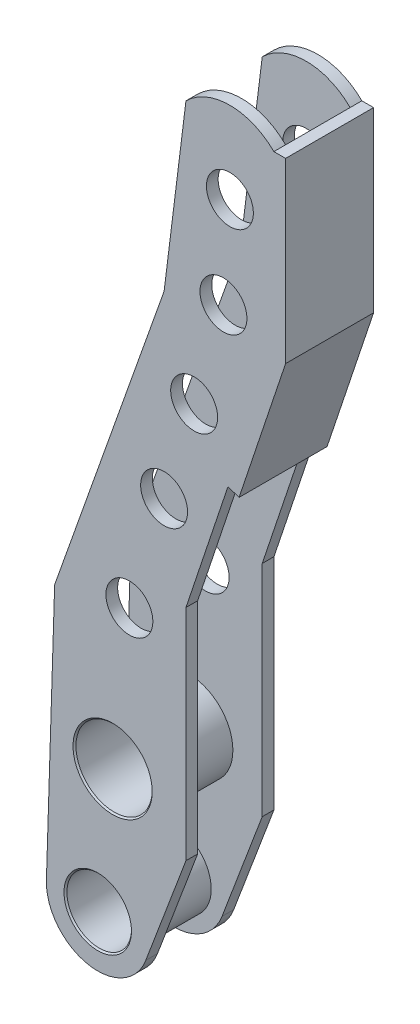
SolidWorks part; units mm, degrees
material "AISI 1020 Steel, Cold Rolled"
ref_plane "Front Plane" through (0, 0, 0) normal (0, 0, 1) x (1, 0, 0)
ref_plane "Top Plane" through (0, 0, 0) normal (0, 1, 0) x (1, 0, 0)
ref_plane "Right Plane" through (0, 0, 0) normal (1, 0, 0) x (0, 0, -1)
sketch "Sketch1" plane through (0, 0, 0) normal (0, 0, 1) x (1, 0, 0)
  line B0 (43.6562, 145.4782) -> (60.0385, 194.4865)
  line B1 (60.0385, 194.4865) -> (60.0385, 254.4271)
  line B2 (30.0781, 254.4271) -> (22.6293, 194.4865)
  line B3 (22.6293, 194.4865) -> (-14.6833, 89.2308)
  line B4 (-14.6833, 89.2308) -> (-14.6833, -0.057)
  line B5 (14.7807, -0.057) -> (30.0781, 30.1029)
  line B6 (30.0781, 30.1029) -> (30.0781, 104.8586)
  line B7 (30.0781, 104.8586) -> (43.6562, 145.4782)
  arc B8 (60.0385, 254.4271) -> (30.0781, 254.4271) centre (45.0583, 239.4469) ccw
  arc B9 (-14.6833, -0.057) -> (14.7807, -0.057) centre (0.0487, -0.057) ccw
  circle B10 centre (-5.2372, 41.2368) radius 3
  circle B11 centre (1.7318, 52.1805) radius 3
  circle B12 centre (21.4304, 50.1742) radius 3
  circle B13 centre (9.5747, 59.1115) radius 3
  circle B14 centre (1.7318, 67.8664) radius 3
  circle B15 centre (-5.2372, 59.1115) radius 3
  circle B16 centre (-4.9682, 76.648) radius 3
  circle B17 centre (10.1372, 104.8586) radius 3.7338
  circle B18 centre (1.7318, 107.7204) radius 4
  circle B19 centre (-4.5729, 25.5702) radius 4
  circle B20 centre (5.6027, 24.4116) radius 4
  circle B21 centre (19.4271, 25.5702) radius 4
  circle B22 centre (0.0487, -0.057) radius 5
  circle B23 centre (10.1372, 81.8976) radius 7.366
  circle B24 centre (22.6293, 133.2845) radius 7.366
  circle B25 centre (32.8774, 166.3648) radius 7.366
  circle B26 centre (42.8552, 200.5742) radius 7.366
  circle B27 centre (45.0583, 232.7881) radius 7.366
sketch_block_instance "break pedal-1"
sketch_block "break pedal"
sketch "Sketch2" plane through (0, 0, 0) normal (0, 0, 1) x (1, 0, 0)
  line L0 (30.0781, 30.1029) -> (30.0781, 104.8586) construction
  line L1 (30.0781, 104.8586) -> (43.6562, 145.4782) construction
  line L2 (43.6562, 145.4782) -> (60.0385, 194.4865) construction
  line L3 (60.0385, 194.4865) -> (60.0385, 254.4271) construction
  line L4 (30.0781, 254.4271) -> (22.6293, 194.4865) construction
  line L5 (22.6293, 194.4865) -> (-14.6833, 89.2308) construction
  line L6 (30.0781, 30.1029) -> (30.0781, 104.8586)
  line L7 (30.0781, 104.8586) -> (43.6562, 145.4782)
  line L8 (43.6562, 145.4782) -> (60.0385, 194.4865)
  line L9 (60.0385, 194.4865) -> (60.0385, 254.4271)
  line L10 (30.0781, 254.4271) -> (22.6293, 194.4865)
  line L11 (22.6293, 194.4865) -> (-14.6833, 89.2308)
  line L12 (30.0781, 30.1029) -> (16.3709, -6.184)
  line L13 (-14.6833, 89.2308) -> (-17.4912, 0.5538)
  line L14 (22.6293, 133.2845) -> (32.8774, 166.3648) construction
  line L15 (32.8774, 166.3648) -> (42.8552, 200.5742) construction
  line L16 (42.8552, 200.5742) -> (45.0583, 232.7881) construction
  line L17 (22.6293, 133.2845) -> (10.7925, 95.0759) construction
  line L18 (0, 0) -> (10.7925, 95.0759) construction
  circle A0 centre (0, 0) radius 12.7
  arc A1 (-17.4912, 0.5538) -> (16.3709, -6.184) centre (0, 0) ccw
  arc A2 (60.0385, 254.4271) -> (30.0781, 254.4271) centre (45.0583, 239.4469) ccw construction
  arc A3 (60.0385, 254.4271) -> (30.0781, 254.4271) centre (45.0583, 239.4469) ccw
  circle A4 centre (45.0583, 232.7881) radius 8
  circle A5 centre (42.8552, 200.5742) radius 8
  circle A6 centre (32.8774, 166.3648) radius 8
  circle A7 centre (22.6293, 133.2845) radius 8
  circle A9 centre (10.7925, 95.0759) radius 8
  circle A10 centre (5.0755, 44.7128) radius 15
  dimension "D1" = 35
  dimension "D2" = 25.4
  dimension "D3" = 16
  dimension "D4" = 40
  dimension "D5" = 45
  dimension "D6" = 30
extrude "Boss-Extrude1" add sketch "Sketch2" along normal blind 4 from offset 11
pattern_linear "LPattern1" count 2 spacing 26 along (0, 0, -1) of "Boss-Extrude1"
sketch "Sketch3" plane through (0, 0, 0) normal (0, 0, 1) x (1, 0, 0)
  line L0 (60.0385, 194.4865) -> (60.0385, 254.4271) construction
  line L1 (30.0781, 104.8586) -> (60.0385, 194.4865) construction
  line L2 (60.0385, 194.4865) -> (60.0385, 254.4271)
  line L3 (44.3933, 147.683) -> (60.0385, 194.4865)
  line L4 (48.1869, 146.4149) -> (64.0385, 193.8356)
  line L5 (64.0385, 193.8356) -> (64.0385, 254.4271)
  line L6 (60.0385, 254.4271) -> (64.0385, 254.4271)
  line L7 (44.3933, 147.683) -> (48.1869, 146.4149)
  line L8 (33.8718, 103.5905) -> (64.0385, 193.8356) construction
  line L9 (30.0781, 104.8586) -> (60.0385, 194.4865) construction
  dimension "D2" = 50
  dimension "D1" = 4
extrude "Boss-Extrude2" add sketch "Sketch3" along normal mid plane 30
chamfer "Chamfer1" [suppressed] distance 4 angle 45
sketch "Sketch4" plane through (0, 0, 0) normal (0, 0, 1) x (1, 0, 0)
  circle A0 centre (0, 0) radius 12.7
  circle A1 centre (5.0755, 44.7128) radius 15
  circle A2 centre (5.0755, 44.7128) radius 15 construction
  circle A3 centre (5.0755, 44.7128) radius 13
  circle A4 centre (0, 0) radius 11
  dimension "D1" = 30
  dimension "D2" = 25.4
  dimension "D3" = 22
  dimension "D4" = 26
extrude "Boss-Extrude3" add sketch "Sketch4" along normal mid plane 30
chamfer "Chamfer2" distance 0.5 angle 45 4 edges at (11, 0, -15) (11, 0, 15) (18.0755, 44.7128, -15) (18.0755, 44.7128, 15)
